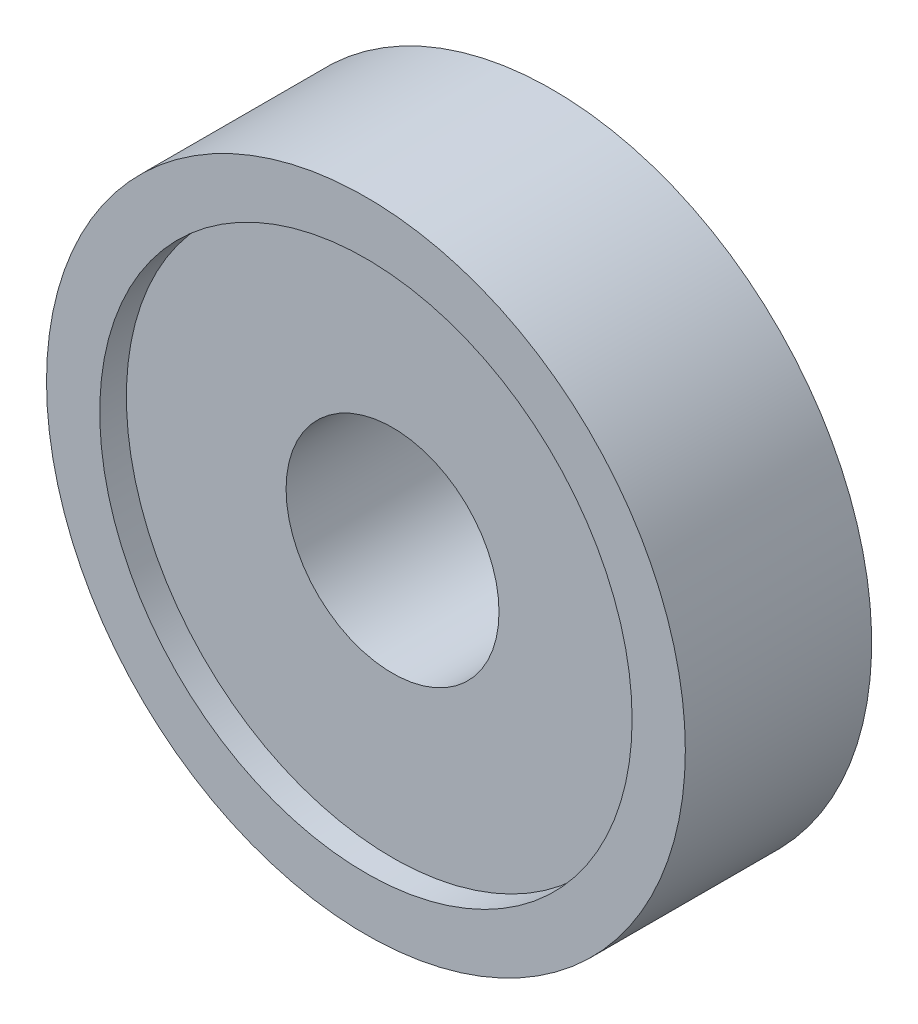
SolidWorks part; units mm, degrees
ref_plane "Front Plane" through (0, 0, 0) normal (1, 0, 0) x (0, 1, 0)
ref_plane "Top Plane" through (0, 0, 0) normal (0, 0, 1) x (0, 1, 0)
ref_plane "Right Plane" through (0, 0, 0) normal (0, 1, 0) x (-1, 0, 0)
sketch "Sketch1" plane through (0, 0, 0) normal (0, 0, 1) x (0, 1, 0)
  circle A0 centre (0, 0) radius 10
  circle A1 centre (0, 0) radius 12
  dimension "D1" = 20
  dimension "D2" = 24
extrude "Boss-Extrude1" add sketch "Sketch1" along normal blind 1
sketch "Sketch2" plane through (0, 0, 0) normal (0, 0, -1) x (1, 0, 0)
  circle A1 centre (0, 0) radius 12
extrude "Boss-Extrude2" add sketch "Sketch2" along normal blind 6
sketch "Sketch3" plane through (0, 0, 0) normal (0, 0, 1) x (1, 0, 0)
  circle A0 centre (0, 0) radius 4
  dimension "D1" = 8
extrude "Cut-Extrude1" cut sketch "Sketch3" against normal blind 13
